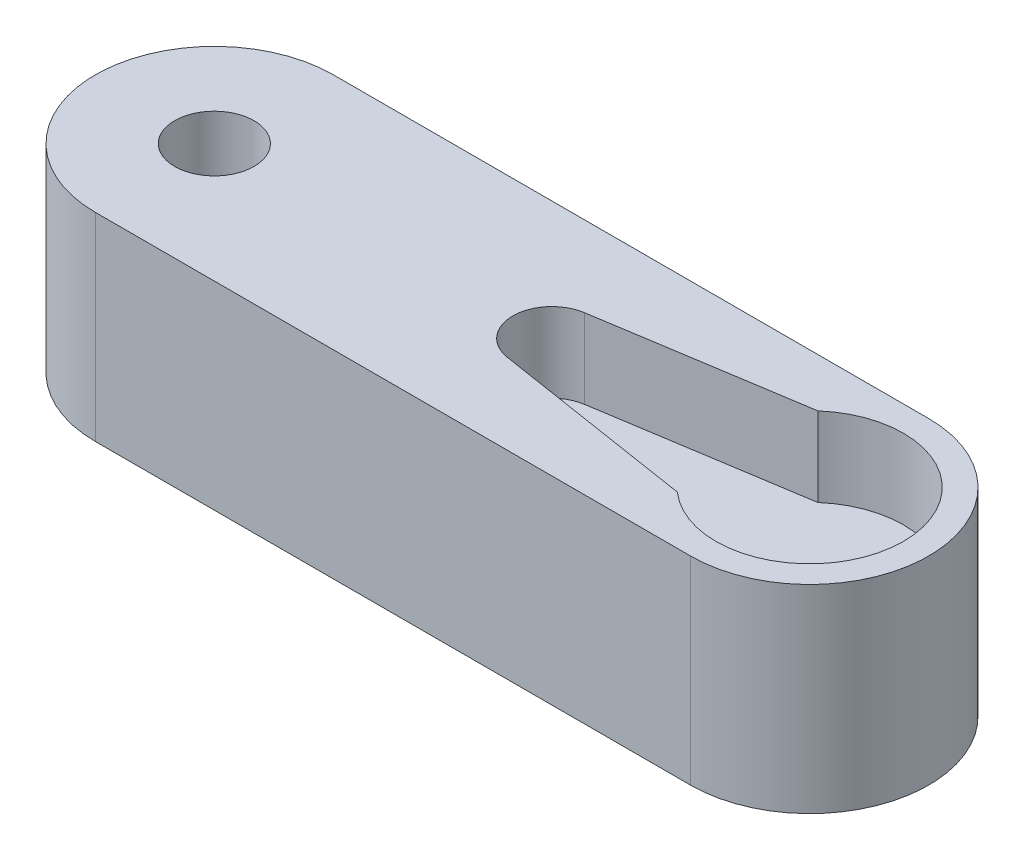
SolidWorks part; units mm, degrees
ref_plane "Front Plane" through (0, 0, 0) normal (0, 0, 1) x (1, 0, 0)
ref_plane "Top Plane" through (0, 0, 0) normal (0, 1, 0) x (1, 0, 0)
ref_plane "Right Plane" through (0, 0, 0) normal (1, 0, 0) x (0, 0, -1)
sketch "Sketch3" plane through (0, 0, 0) normal (0, 1, 0) x (1, 0, 0)
  line L0 (-31.75, 0) -> (6.35, 0) construction
  line L1 (-6.985, 0) -> (6.985, 0) construction
  line L2 (-31.75, 7.62) -> (6.35, 7.62)
  line L3 (-31.75, -7.62) -> (6.35, -7.62)
  arc A0 (-31.75, 7.62) -> (-31.75, -7.62) centre (-31.75, 0) ccw
  arc A1 (6.35, -7.62) -> (6.35, 7.62) centre (6.35, 0) ccw
  point P5 (-12.7, 0)
  dimension "D2" = 7.62
  dimension "D1" = 38.1
  dimension "D3" = 31.75
extrude "Boss-Extrude1" add sketch "Sketch3" along normal blind 12.7
sketch "Sketch4" plane through (0, 12.7, 0) normal (0, 1, 0) x (1, 0, 0)
  circle A0 centre (-31.75, 0) radius 2.54
  dimension "D1" = 5.08
extrude "Cut-Extrude3" cut sketch "Sketch4" against normal through all
sketch "Sketch5" plane through (0, 12.7, 0) normal (0, 1, 0) x (1, 0, 0)
  line L0 (-10.5381, -2.4697) -> (2.3814, -4.5)
  line L1 (2.3814, 4.5) -> (-10.5381, 2.4697)
  arc A0 (-10.5381, 2.4697) -> (-10.5381, -2.4697) centre (-10.15, 0) ccw
  arc A1 (2.3814, -4.5) -> (2.3814, 4.5) centre (6.35, 0) ccw
  dimension "D1" = 38.1
extrude "Cut-Extrude4" cut sketch "Sketch5" against normal blind 5.08
equation "\"TibiaLength\"= 5in"
equation "\"TibiaRadius\"= 0.3in"
equation "\"TibiaDistFromCentre\"= \"TibiaLength\" / 2"
equation "\"TibiaThickness\"= 0.5in"
equation "\"HoleRadius\"= 0.2in"
equation "\"D1@Sketch3\"= \"TibiaLength\" * 0.3"
equation "\"D2@Sketch3\"= \"TibiaRadius\""
equation "\"D3@Sketch3\"=\"TibiaDistFromCentre\"/2"
equation "\"D1@Boss-Extrude1\"= \"TibiaThickness\""
equation "\"D1@Sketch4\"= \"HoleRadius\""
equation "\"D1@Sketch5\"=\"TibiaLength\"*0.3"
